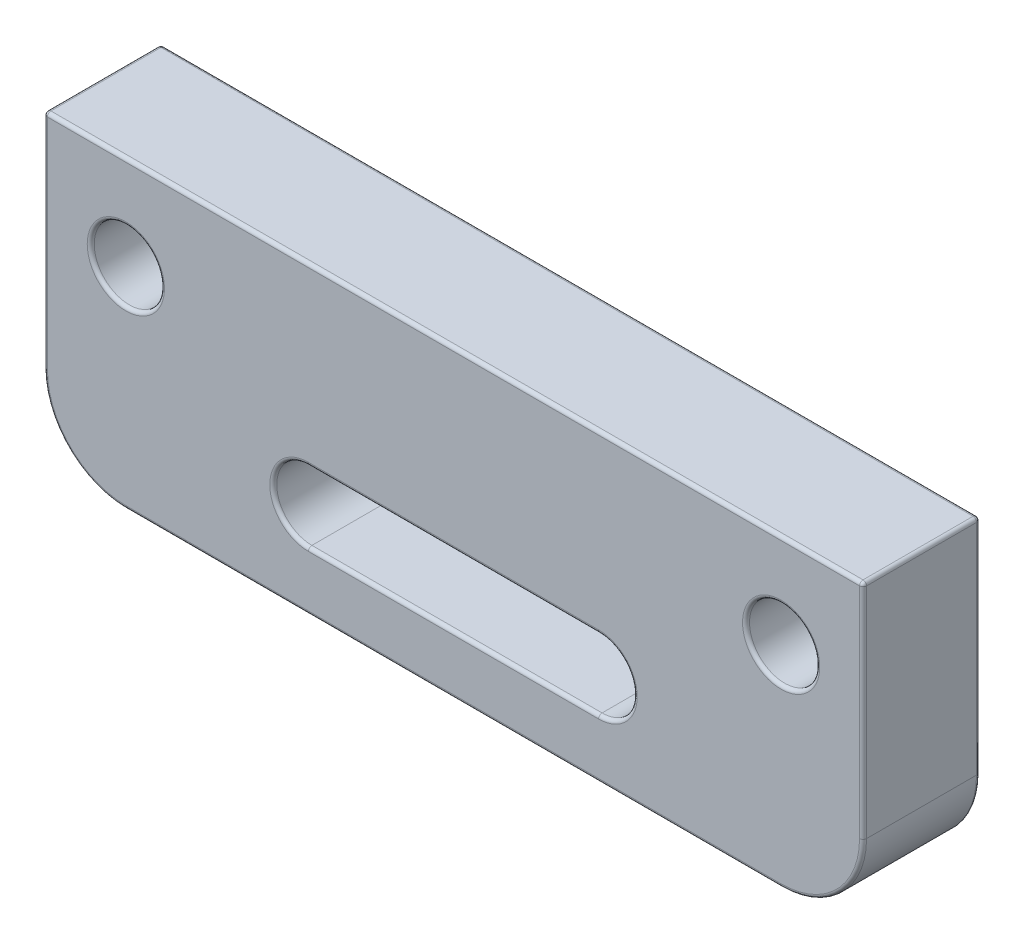
SolidWorks part; units mm, degrees
material "AISI 1020"
ref_plane "Front Plane" through (0, 0, 0) normal (0, 0, 1) x (1, 0, 0)
ref_plane "Top Plane" through (0, 0, 0) normal (0, 1, 0) x (1, 0, 0)
ref_plane "Right Plane" through (0, 0, 0) normal (1, 0, 0) x (0, 0, -1)
sketch "Sketch1" plane through (0, 0, 0) normal (0, 0, 1) x (1, 0, 0)
  line L0 (0, -19) -> (0, 26) construction
  line L1 (11.5, -6) -> (-11.5, -6)
  line L2 (11.5, -6) -> (11.5, 6)
  line L3 (11.5, 6) -> (-11.5, 6)
  line L4 (-11.5, -6) -> (-11.5, 6)
  line L5 (11.5, -6) -> (-11.5, 6) construction
  line L6 (11.5, 6) -> (-11.5, -6) construction
  line L7 (-6.2, -15) -> (6.2, -15) construction
  line L8 (-6.2, -13.5) -> (6.2, -13.5)
  line L9 (-6.2, -16.5) -> (6.2, -16.5)
  line L11 (-17.5, 9) -> (17.5, 9) construction
  line L12 (-17.5, 9) -> (-17.5, -19)
  line L13 (-17.5, -19) -> (17.5, -19)
  line L14 (17.5, 9) -> (17.5, -19)
  circle A0 centre (-14, 0) radius 1
  circle A1 centre (-14, -10) radius 1.5
  arc A2 (-6.2, -13.5) -> (-6.2, -16.5) centre (-6.2, -15) ccw
  arc A3 (6.2, -16.5) -> (6.2, -13.5) centre (6.2, -15) ccw
  circle A4 centre (-8.5, 16) radius 2
  circle A5 centre (14, -10) radius 1.5
  circle A6 centre (14, 0) radius 1
  circle A7 centre (8.5, 16) radius 2
  arc A8 (-17.5, 9) -> (17.5, 9) centre (0, 8.4926) cw
  point P0 (0, 0)
  point P10 (-11.5, 0)
  point P11 (0, -15)
  point P33 (0, 26)
  dimension "D5" = 2
  dimension "D7" = 3
  dimension "D9" = 1.5
  dimension "D12" = 10
  dimension "D13" = 4
  dimension "D1" = 23
  dimension "D2" = 12
  dimension "D3" = 45
  dimension "D4" = 13
  dimension "D6" = 2.5
  dimension "D8" = 10
  dimension "D10" = 12.4
  dimension "D11" = 4
  dimension "D14" = 8.5
  dimension "D15" = 28
  dimension "D16" = 35
  dimension "D17" = 13
extrude "Boss-Extrude1" add sketch "Sketch1" along normal blind 5
fillet "Fillet1" radius 3.5 2 edges at (17.5, -19, 2.5) (-17.5, -19, 2.5)
sketch "Sketch2" plane through (0, 0, 5) normal (0, 0, 1) x (1, 0, 0)
  line L0 (-22.5, -6) -> (27.5, -6)
  line L3 (-11.5, -6) -> (11.5, -6) construction
  line L4 (-17.5, 9) -> (-17.5, -15.5) construction
  dimension "D1" = 50
  dimension "D2" = 5
extrude "Cut-Extrude1" cut sketch "Sketch2" against normal through all both and the other way through all
fillet "Fillet3" radius 0.15 26 edges at (-16.4749, -17.9749, 0) (0, -19, 0) (16.4749, -17.9749, 0) (17.5, -10.75, 0) (0, -6, 0) (-17.5, -10.75, 0) (-12.5, -10, 0) (7.7, -15, 0) (0, -16.5, 0) (-7.7, -15, 0) (0, -13.5, 0) (12.5, -10, 0) (17.5, -10.75, 5) (16.4749, -17.9749, 5) (0, -19, 5) (-16.4749, -17.9749, 5) (-17.5, -10.75, 5) (0, -6, 5) (-12.5, -10, 5) (0, -16.5, 5) (7.7, -15, 5) (0, -13.5, 5) (-7.7, -15, 5) (12.5, -10, 5) (17.5, -6, 2.5) (-17.5, -6, 2.5)
